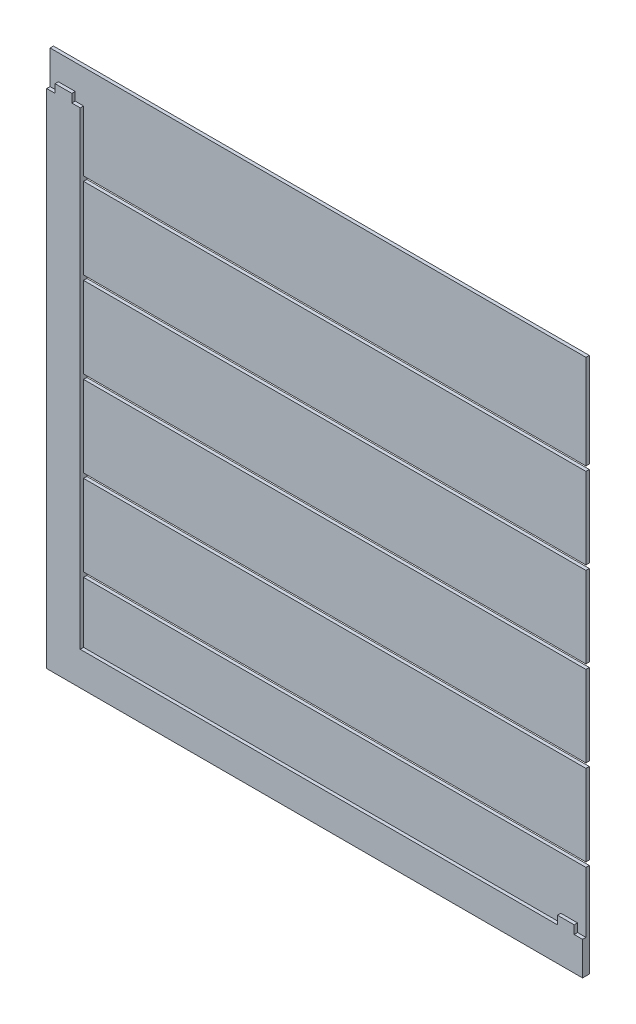
SolidWorks part; units mm, degrees
ref_plane "前视基准面" through (0, 0, 0) normal (0, 0, 1) x (1, 0, 0)
ref_plane "上视基准面" through (0, 0, 0) normal (0, 1, 0) x (1, 0, 0)
ref_plane "右视基准面" through (0, 0, 0) normal (1, 0, 0) x (0, 0, -1)
sketch "草图1" plane through (0, 0, 0) normal (0, 0, 1) x (1, 0, 0)
  line L0 (-75, 51.8686) -> (75, 51.8686)
  line L5 (75, 79.9686) -> (75, 51.8686)
  line L6 (75, 50.4686) -> (75, 26.2686)
  line L7 (-75, 50.4686) -> (75, 50.4686)
  line L8 (75, 24.8686) -> (75, 0.6686)
  line L9 (-75, 50.4686) -> (-75, 51.8686)
  line L10 (-75, 51.8686) -> (-75, 51.1686) construction
  line L11 (-75, 51.1686) -> (75, 51.1686) construction
  line L12 (-75, 51.8686) -> (75, 51.8686)
  line L13 (-75, 24.8686) -> (-75, 26.2686)
  line L14 (75, -0.7314) -> (75, -24.9314)
  line L15 (75, -26.3314) -> (75, -50.5314)
  line L16 (-65, 51.8686) -> (75, 51.8686)
  line L17 (-65, 50.4686) -> (75, 50.4686)
  line L18 (75, -51.9314) -> (75, -80.0314)
  line L19 (-65, 51.8686) -> (75, 51.8686)
  line L20 (-75, -0.7314) -> (-75, 0.6686)
  line L21 (-65, 51.1686) -> (75, 51.1686) construction
  line L22 (75, 79.9686) -> (-85, 79.9686)
  line L23 (-85, 79.9686) -> (-85, -80.0314)
  line L24 (-65, 26.2686) -> (75, 26.2686)
  line L25 (-65, 24.8686) -> (75, 24.8686)
  line L27 (-65, 26.2686) -> (75, 26.2686)
  line L29 (-65, 25.5686) -> (75, 25.5686) construction
  line L30 (-85, -80.0314) -> (75, -80.0314)
  line L32 (-65, 0.6686) -> (75, 0.6686)
  line L33 (-65, -0.7314) -> (75, -0.7314)
  line L35 (-65, 0.6686) -> (75, 0.6686)
  line L37 (-65, -0.0314) -> (75, -0.0314) construction
  line L45 (-65, -25.6314) -> (75, -25.6314) construction
  line L47 (-75, -26.3314) -> (-75, -24.9314)
  line L50 (-75, -0.0314) -> (-85, -0.0314) construction
  line L54 (-75, -51.9314) -> (-75, -50.5314)
  line L56 (-75, 26.2686) -> (75, 26.2686)
  line L57 (-75, 24.8686) -> (75, 24.8686)
  line L59 (-75, 26.2686) -> (75, 26.2686)
  line L61 (-75, 25.5686) -> (75, 25.5686) construction
  line L64 (-75, 0.6686) -> (75, 0.6686)
  line L65 (-75, -0.7314) -> (75, -0.7314)
  line L67 (-75, 0.6686) -> (75, 0.6686)
  line L69 (-75, -0.0314) -> (75, -0.0314) construction
  line L72 (-75, -24.9314) -> (75, -24.9314)
  line L73 (-75, -26.3314) -> (75, -26.3314)
  line L75 (-75, -24.9314) -> (75, -24.9314)
  line L77 (-75, -25.6314) -> (75, -25.6314) construction
  line L80 (-75, -50.5314) -> (75, -50.5314)
  line L81 (-75, -51.9314) -> (75, -51.9314)
  line L83 (-75, -50.5314) -> (75, -50.5314)
  line L85 (-75, -51.2314) -> (75, -51.2314) construction
  line L101 (-65, -26.3314) -> (75, -26.3314) [skipped]
  line L102 (-65, -24.9314) -> (75, -24.9314) [skipped]
  line L103 (-65, -24.9314) -> (75, -24.9314) [skipped]
  line L105 (-65, -50.5314) -> (75, -50.5314) [skipped]
  line L106 (-65, -50.5314) -> (75, -50.5314) [skipped]
  line L107 (-65, -51.9314) -> (75, -51.9314) [skipped]
  line L108 (-65, -51.2314) -> (75, -51.2314) construction
  point P0 (0, 0)
  point P3 (-85, -0.0314)
  dimension "D1" = 160
  dimension "D3" = 1.4
  dimension "D5" = 2
  dimension "D7" = 25.6
  dimension "D6" = 5
extrude "凸台-拉伸1" add sketch "草图1" along normal blind 1
sketch "草图2" plane through (0, 0, 1) normal (0, 0, 1) x (1, 0, 0)
  line L0 (-85, -80.0314) -> (-85, -70.0314)
  line L1 (-85, 79.9686) -> (-85, -80.0314) construction
  line L2 (-75, -70.0314) -> (67.5, -70.0314)
  line L3 (75, -80.0314) -> (75, -51.9314) construction
  line L4 (75, -70.0314) -> (75, -80.0314)
  line L5 (75, -80.0314) -> (-85, -80.0314)
  line L6 (-75, -70.0314) -> (-75, 69.9686)
  line L7 (-80, 72.4686) -> (-80, 75.0021) construction
  line L9 (-85, 69.9686) -> (-85, -70.0314)
  line L10 (-85, 69.9686) -> (-82.5, 69.9686)
  line L11 (-82.5, 69.9686) -> (-82.5, 72.4686)
  line L12 (-82.5, 72.4686) -> (-77.5, 72.4686)
  line L13 (-77.5, 69.9686) -> (-75, 69.9686)
  line L14 (75, 79.9686) -> (-85, 79.9686) construction
  line L15 (-77.5, 69.9686) -> (-77.5, 72.4686)
  line L16 (72.5, -70.0314) -> (72.5, -67.5314)
  line L17 (72.5, -67.5314) -> (67.5, -67.5314)
  line L18 (67.5, -67.5314) -> (67.5, -70.0314)
  line L19 (75, -51.9314) -> (75, -80.0314) construction
  line L20 (72.5, -70.0314) -> (75, -70.0314)
  dimension "D1" = 10
  dimension "D2" = 10
  dimension "D3" = 5
  dimension "D4" = 2.5
  dimension "D5" = 10
  dimension "D6" = 2.5
  dimension "D7" = 2.5
extrude "凸台-拉伸2" add sketch "草图2" along normal blind 1
